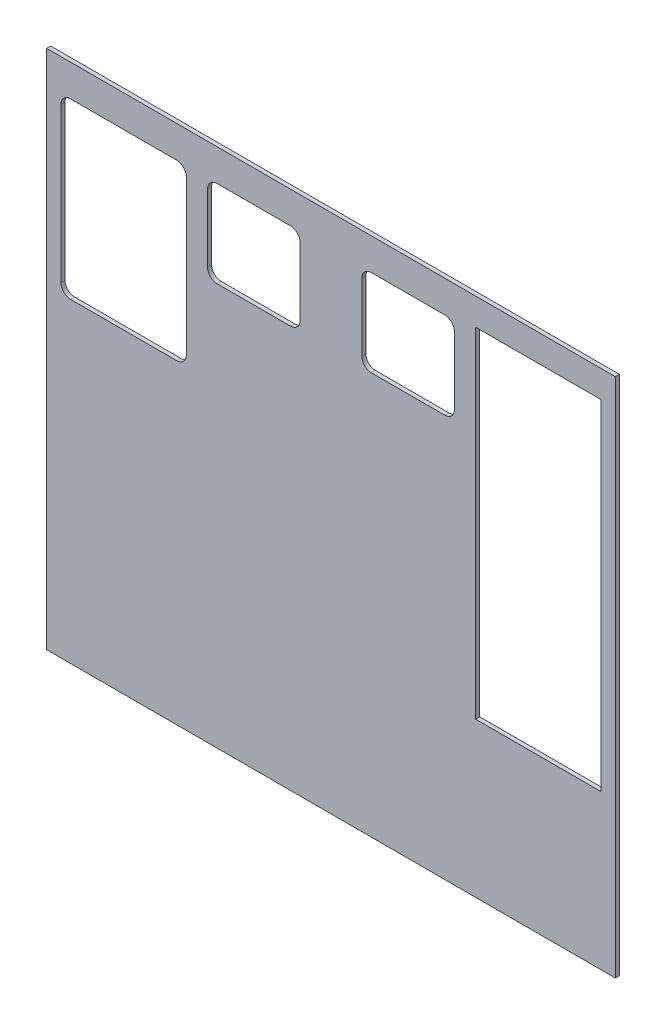
SolidWorks part; units mm, degrees
material "ASTM A36 Steel"
ref_plane "Front Plane" through (0, 0, 0) normal (0, 0, 1) x (1, 0, 0)
ref_plane "Top Plane" through (0, 0, 0) normal (0, 1, 0) x (1, 0, 0)
ref_plane "Right Plane" through (0, 0, 0) normal (1, 0, 0) x (0, 0, -1)
sketch "Sketch1" plane through (0, 0, 0) normal (0, 0, 1) x (1, 0, 0)
  line L0 (-193.04, 0) -> (-193.04, 349.25)
  line L1 (0, 0) -> (0, 358.775) construction
  line L2 (193.04, 0) -> (-193.04, 0)
  line L3 (193.04, 0) -> (193.04, 349.25)
  line L4 (74.93, 264.795) -> (26.67, 264.795)
  line L5 (-171.45, 321.945) -> (-101.6, 321.945)
  line L6 (-177.8, 315.595) -> (-177.8, 213.995)
  line L7 (-171.45, 207.645) -> (-101.6, 207.645)
  line L8 (-95.25, 315.595) -> (-95.25, 213.995)
  line L9 (-74.93, 321.945) -> (-26.67, 321.945)
  line L10 (-81.28, 315.595) -> (-81.28, 271.145)
  line L11 (-74.93, 264.795) -> (-26.67, 264.795)
  line L12 (-20.32, 315.595) -> (-20.32, 271.145)
  line L17 (95.25, 325.12) -> (177.8, 325.12)
  line L18 (95.25, 325.12) -> (95.25, 101.6)
  line L19 (95.25, 101.6) -> (177.8, 101.6)
  line L20 (177.8, 325.12) -> (177.8, 101.6)
  line L21 (20.32, 315.595) -> (20.32, 271.145)
  line L22 (74.93, 321.945) -> (26.67, 321.945)
  line L23 (81.28, 315.595) -> (81.28, 271.145)
  arc A0 (193.04, 349.25) -> (-193.04, 349.25) centre (0, -1602.1262) ccw
  arc A1 (-101.6, 207.645) -> (-95.25, 213.995) centre (-101.6, 213.995) ccw
  arc A2 (-95.25, 315.595) -> (-101.6, 321.945) centre (-101.6, 315.595) ccw
  arc A3 (-177.8, 213.995) -> (-171.45, 207.645) centre (-171.45, 213.995) ccw
  arc A4 (-171.45, 321.945) -> (-177.8, 315.595) centre (-171.45, 315.595) ccw
  arc A5 (-20.32, 315.595) -> (-26.67, 321.945) centre (-26.67, 315.595) ccw
  arc A6 (-26.67, 264.795) -> (-20.32, 271.145) centre (-26.67, 271.145) ccw
  arc A7 (-81.28, 271.145) -> (-74.93, 264.795) centre (-74.93, 271.145) ccw
  arc A8 (-74.93, 321.945) -> (-81.28, 315.595) centre (-74.93, 315.595) ccw
  arc A9 (81.28, 271.145) -> (74.93, 264.795) centre (74.93, 271.145) cw
  arc A10 (26.67, 264.795) -> (20.32, 271.145) centre (26.67, 271.145) cw
  arc A11 (20.32, 315.595) -> (26.67, 321.945) centre (26.67, 315.595) cw
  arc A12 (74.93, 321.945) -> (81.28, 315.595) centre (74.93, 315.595) cw
  point P28 (-95.25, 321.945)
  point P31 (-177.8, 207.645)
  point P34 (-177.8, 321.945)
  point P37 (-20.32, 321.945)
  point P42 (-81.28, 264.795)
  point P45 (-81.28, 321.945)
  point P60 (193.04, 349.25)
  point P64 (-193.04, 349.25)
  dimension "D1" = 358.775
  dimension "D12" = 20.32
  dimension "D16" = 101.6
  dimension "D8" = 6.35
  dimension "D11" = 6.35
  dimension "D2" = 349.25
  dimension "D3" = 386.08
  dimension "D4" = 82.55
  dimension "D5" = 114.3
  dimension "D6" = 207.645
  dimension "D7" = 95.25
  dimension "D9" = 57.15
  dimension "D10" = 60.96
  dimension "D13" = 15.24
  dimension "D14" = 13.97
  dimension "D15" = 223.52
extrude "Boss-Extrude1" add sketch "Sketch1" along normal blind 2.667
sketch "Sketch2" plane through (0, 0, 2.667) normal (0, 0, 1) x (1, 0, 0)
  line L0 (-193.04, 0) -> (-193.04, 349.25) construction
  line L1 (193.04, 0) -> (193.04, 349.25) construction
  line L2 (-187.198, 342.9) -> (187.198, 342.9)
  line L4 (-187.198, 0) -> (-187.198, 342.9)
  line L5 (187.198, 0) -> (187.198, 342.9)
  line L6 (-20.32, 315.595) -> (-20.32, 271.145) construction
  line L7 (193.04, 0) -> (-193.04, 0) construction
  line L8 (0, 0) -> (0, 358.775) construction
  arc A0 (193.04, 349.25) -> (-193.04, 349.25) centre (0, -1602.1262) ccw construction
  line M17 (-193.04, 0) -> (193.04, 0)
  line M18 (193.04, 0) -> (193.04, 349.25)
  arc M19 (193.04, 349.25) -> (-193.04, 349.25) centre (0, -1602.1262) ccw
  line M20 (-193.04, 349.25) -> (-193.04, 0)
  dimension "D1" = 342.9
  dimension "D2" = 374.396
extrude "CornerRadiusAllowance" cut sketch "Sketch2" against normal through all contours L2 L8 L4 M19 M20 M17 | L8 L2 L5 M17 M18 M19
